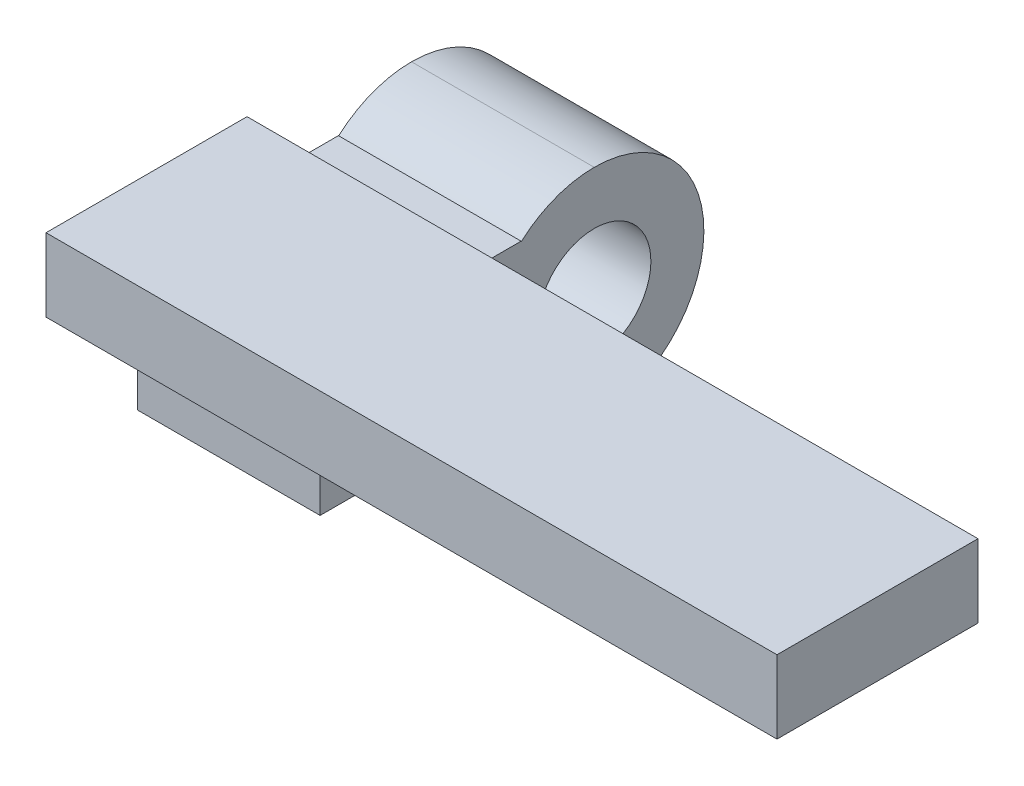
SolidWorks part; units mm, degrees
material "Plain Carbon Steel"
ref_plane "Front Plane" through (0, 0, 0) normal (0, 0, 1) x (1, 0, 0)
ref_plane "Top Plane" through (0, 0, 0) normal (0, 1, 0) x (1, 0, 0)
ref_plane "Right Plane" through (0, 0, 0) normal (1, 0, 0) x (0, 0, -1)
sketch "Sketch1" plane through (0, 0, 0) normal (0, 0, 1) x (1, 0, 0)
  line L0 (-5, 0) -> (5, 0) construction
  line L1 (-5, 3.1) -> (5, 3.1)
  line L2 (5, 3.1) -> (5, 6)
  line L3 (5, 6) -> (-5, 6)
  line L4 (-5, 6) -> (-5, 3.1)
revolve "Revolve1" add sketch "Sketch1" angle 360 about L0
sketch "Sketch2" plane through (0, 0, 0) normal (0, 1, 0) x (1, 0, 0)
  line L0 (-5, -15) -> (5, -15)
  line L1 (5, -15) -> (5, -4)
  line L2 (5, -6) -> (5, 6) construction
  line L3 (5, -4) -> (-5, -4)
  line L4 (-5, 6) -> (-5, -6) construction
  line L5 (-5, -4) -> (-5, -15)
extrude "Boss-Extrude1" add sketch "Sketch2" along normal blind 7.5 from offset 3
sketch "Sketch3" plane through (0, 0, 0) normal (0, 1, 0) x (1, 0, 0)
  line L0 (-5, -20) -> (35, -20)
  line L1 (35, -20) -> (35, -9)
  line L2 (35, -9) -> (-5, -9)
  line L3 (-5, -4) -> (-5, -15) construction
  line L4 (-5, -9) -> (-5, -20)
extrude "Boss-Extrude2" add sketch "Sketch3" along normal blind 4 from offset 3.9
